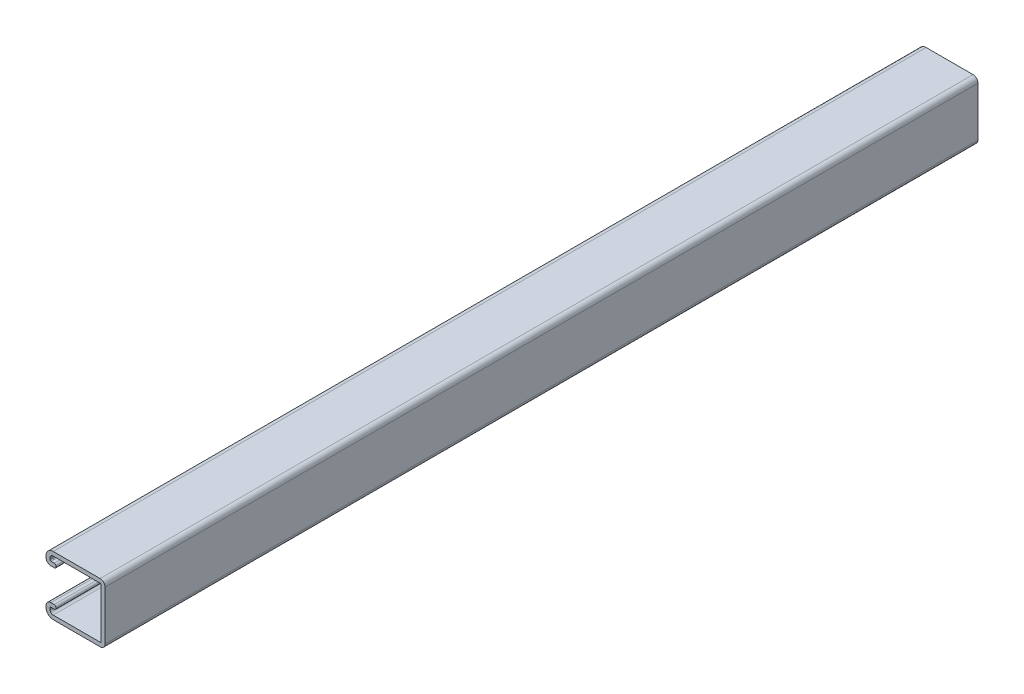
SolidWorks part; units mm, degrees
ref_plane "Front Plane" through (0, 0, 0) normal (0, 0, 1) x (1, 0, 0)
ref_plane "Top Plane" through (0, 0, 0) normal (0, 1, 0) x (1, 0, 0)
ref_plane "Right Plane" through (0, 0, 0) normal (1, 0, 0) x (0, 0, -1)
sketch "Sketch1" plane through (0, 0, 0) normal (0, 0, 1) x (1, 0, 0)
  line L0 (0, 0) -> (-41.275, 0) construction
  line L3 (-41.275, 20.6375) -> (0, 20.6375) construction
  line L4 (-41.275, 20.6375) -> (-41.275, -20.6375) construction
  line L5 (-41.275, -20.6375) -> (0, -20.6375) construction
  line L6 (0, 20.6375) -> (0, -20.6375) construction
  line L7 (-36.2267, 20.6375) -> (-3.4607, 20.6375)
  line L8 (0, 17.1767) -> (0, -17.1767)
  line L9 (-2.794, -17.1767) -> (-2.794, 17.1767)
  line L10 (-3.4608, 17.8435) -> (-36.2267, 17.8435)
  line L11 (-41.275, 15.5892) -> (-41.275, 14.5732)
  line L12 (-37.8142, 11.1125) -> (-35.5346, 11.1125)
  line L14 (-35.5346, 13.9065) -> (-37.8142, 13.9065)
  line L15 (-38.481, 14.5732) -> (-38.481, 15.5892)
  line L16 (-38.481, -14.5733) -> (-38.481, -15.5893)
  line L17 (-35.5346, -13.9065) -> (-37.8142, -13.9065)
  line L18 (-37.8142, -11.1125) -> (-35.5346, -11.1125)
  line L19 (-41.275, -15.5893) -> (-41.275, -14.5733)
  line L20 (-3.4607, -17.8435) -> (-36.2267, -17.8435)
  line L21 (-36.2267, -20.6375) -> (-3.4607, -20.6375)
  line L22 (-2.794, -20.6375) -> (-2.794, 20.6375) construction
  arc A1 (0, 17.1767) -> (-3.4607, 20.6375) centre (-3.4607, 17.1767) ccw
  arc A2 (-2.794, 17.1767) -> (-3.4608, 17.8435) centre (-3.4607, 17.1767) ccw
  arc A4 (-36.2267, 20.6375) -> (-41.275, 15.5892) centre (-36.2267, 15.5892) ccw
  arc A5 (-41.275, 14.5732) -> (-37.8142, 11.1125) centre (-37.8142, 14.5732) ccw
  arc A6 (-35.5346, 11.1125) -> (-35.5346, 13.9065) centre (-35.5346, 12.5095) ccw
  arc A7 (-37.8142, 13.9065) -> (-38.481, 14.5732) centre (-37.8142, 14.5732) cw
  arc A8 (-38.481, 15.5892) -> (-36.2267, 17.8435) centre (-36.2267, 15.5892) cw
  arc A9 (-38.481, -15.5893) -> (-36.2267, -17.8435) centre (-36.2267, -15.5893) ccw
  arc A10 (-37.8142, -13.9065) -> (-38.481, -14.5733) centre (-37.8142, -14.5733) ccw
  arc A11 (-35.5346, -11.1125) -> (-35.5346, -13.9065) centre (-35.5346, -12.5095) cw
  arc A12 (-41.275, -14.5733) -> (-37.8142, -11.1125) centre (-37.8142, -14.5733) cw
  arc A13 (-36.2267, -20.6375) -> (-41.275, -15.5893) centre (-36.2267, -15.5893) cw
  arc A14 (-2.794, -17.1767) -> (-3.4607, -17.8435) centre (-3.4607, -17.1767) cw
  arc A15 (0, -17.1767) -> (-3.4607, -20.6375) centre (-3.4607, -17.1767) cw
  point P24 (0, 20.6375)
  point P65 (-2.794, 0)
  dimension "D1" = 3.4608
  dimension "D2" = 5.0482
  dimension "D3" = 3.4608
  dimension "Ht." = 41.275
  dimension "Wd." = 41.275
  dimension "Thk." = 2.794
  dimension "D4" = 9.525
  dimension "D5" = 7.1374
extrude "Boss-Extrude1" add sketch "Sketch1" against normal blind 609.6
